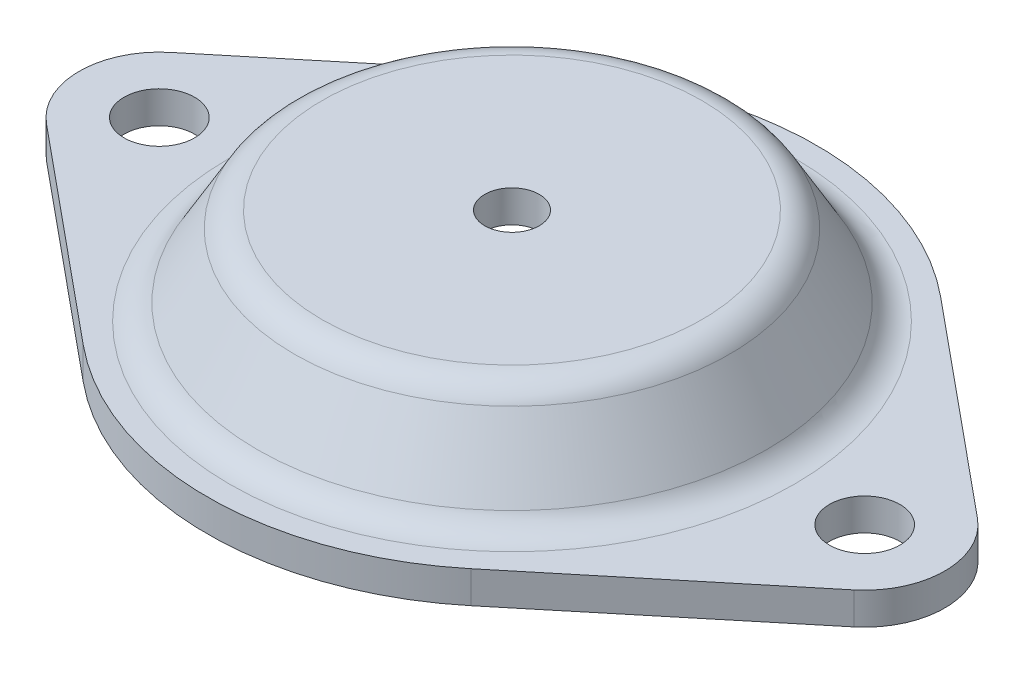
SolidWorks part; units mm, degrees
material "1.0037 (S235JR)"
ref_plane "Płaszczyzna przednia" through (0, 0, 0) normal (0, 0, 1) x (1, 0, 0)
ref_plane "Płaszczyzna górna" through (0, 0, 0) normal (0, 1, 0) x (1, 0, 0)
ref_plane "Płaszczyzna prawa" through (0, 0, 0) normal (1, 0, 0) x (0, 0, -1)
sketch "Szkic1" plane through (0, 0, 0) normal (0, 0, 1) x (1, 0, 0)
  line L0 (0, 100.3333) -> (0, -87) construction
  line L1 (0, 0) -> (-32.5, 0)
  line L2 (-32.5, 0) -> (-41.1603, -15)
  line L3 (-41.1603, -15) -> (-67.5, -15)
  line L4 (-67.5, -15) -> (-67.5, -20)
  line L5 (-67.5, -20) -> (-38.2735, -20)
  line L6 (-38.2735, -20) -> (-29.6132, -5)
  line L7 (-29.6132, -5) -> (0, -5)
  line L8 (0, 0) -> (0, -5)
  dimension "D1" = 5
  dimension "D2" = 5
  dimension "D3" = 5
  dimension "D4" = 135
  dimension "D5" = 65
  dimension "D6" = 15
  dimension "D7" = 120
revolve "Obrót1" add sketch "Szkic1" angle 360 about L0
fillet "Zaokrąglenie1" radius 5 4 edges at (0, -20, 38.2735) (0, -5, 29.6132) (0, -15, 41.1603) (0, 0, 32.5)
sketch "Szkic2" plane through (0, 0, 0) normal (0, 1, 0) x (1, 0, 0)
  circle A0 centre (-55, 0) radius 5.5
  circle A1 centre (55, 0) radius 5.5
  dimension "D1" = 11
  dimension "D2" = 11
  dimension "D3" = 110
  dimension "D4" = 55
extrude "Wytnij-wyciągnięcie1" cut sketch "Szkic2" against normal through all
hole_wizard "Otwór gwintowany M101" positions "Szkic3" profile "Szkic4" tap size "M10" standard "ISO"
sketch "Szkic3" plane through (0, 0, 0) normal (0, 1, 0) x (1, 0, 0)
  point P0 (0, 0)
sketch "Szkic4" plane through (0, 0, 0) normal (1, 0, 0) x (0, 0, 1)
  line L0 (0, 0) -> (0, 20.0537)
  line L1 (0, 20.0537) -> (4.25, 17.5)
  line L2 (4.25, 17.5) -> (4.25, 0)
  line L5 (4.25, 0) -> (0, 0)
  line L10 (0, 20.0537) -> (-4.25, 17.5) construction
  line L11 (0, -6.35) -> (0, 107.95) construction
  dimension "Średnica wiertła gwintu" = 8.5
  dimension "Głębokość otworu gwintowanego" = 17.5
  dimension "Kąt wiertła" = 118
cosmetic thread "Gwint otworu1" parameters "D1"=5, "D2"=10
sketch "Szkic5" plane through (0, -15, 0) normal (0, 1, 0) x (1, 0, 0)
  line L0 (62.9545, 9.6424) -> (30.2273, 36.641)
  line L1 (-62.9545, 9.6424) -> (-30.2273, 36.641)
  line L2 (-62.9545, -9.6424) -> (-30.2273, -36.641)
  line L3 (62.9545, -9.6424) -> (30.2273, -36.641)
  arc A0 (-30.2273, -36.641) -> (30.2273, -36.641) centre (0, 0) ccw
  arc A1 (-62.9545, 9.6424) -> (-62.9545, -9.6424) centre (-55, 0) ccw
  arc A2 (62.9545, -9.6424) -> (62.9545, 9.6424) centre (55, 0) ccw
  circle A3 centre (0, 0) radius 67.5 construction
  arc A4 (30.2273, 36.641) -> (-30.2273, 36.641) centre (0, 0) ccw
  dimension "D1" = 95
extrude "Wytnij-wyciągnięcie2" cut sketch "Szkic5" against normal through all and the other way through all flip side to cut
